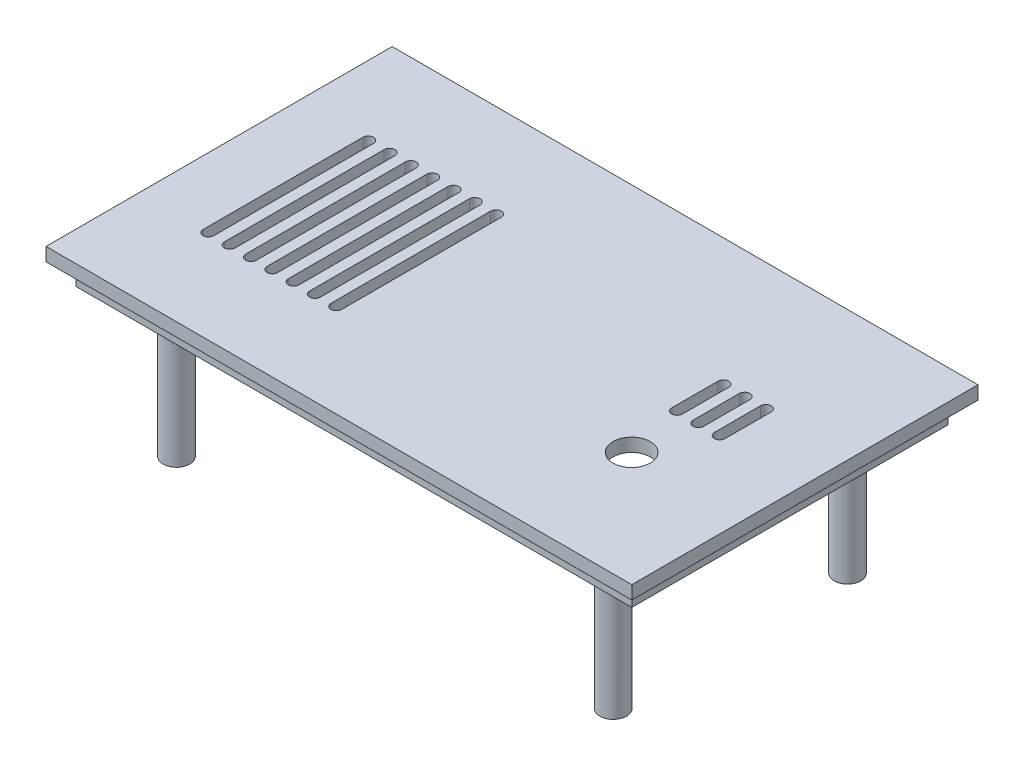
SolidWorks part; units mm, degrees
ref_plane "Front Plane" through (0, 0, 0) normal (0, 0, 1) x (1, 0, 0)
ref_plane "Top Plane" through (0, 0, 0) normal (0, 1, 0) x (1, 0, 0)
ref_plane "Right Plane" through (0, 0, 0) normal (1, 0, 0) x (0, 0, -1)
sketch "Croquis_tapa" plane through (0, 0, 0) normal (0, 1, 0) x (1, 0, 0)
  line L1 (-55, -32.5) -> (55, -32.5)
  line L2 (-55, -32.5) -> (-55, 32.5)
  line L3 (-55, 32.5) -> (55, 32.5)
  line L4 (55, -32.5) -> (55, 32.5)
  line L5 (-55, -32.5) -> (55, 32.5) construction
  line L6 (-55, 32.5) -> (55, -32.5) construction
  point P0 (0, 0)
  dimension "D1" = 110
  dimension "D2" = 65
extrude "Tapa" add sketch "Croquis_tapa" along normal blind 2.5
sketch "Croquis_pestana" plane through (0, 0, 0) normal (0, 1, 0) x (1, 0, 0)
  line L1 (-52.2, -29.7) -> (52.2, -29.7)
  line L2 (-52.2, -29.7) -> (-52.2, 29.7)
  line L3 (-52.2, 29.7) -> (52.2, 29.7)
  line L4 (52.2, -29.7) -> (52.2, 29.7)
  line L5 (-52.2, -29.7) -> (52.2, 29.7) construction
  line L6 (-52.2, 29.7) -> (52.2, -29.7) construction
  dimension "D1" = 104.4
  dimension "D2" = 59.4
extrude "Pestana" add sketch "Croquis_pestana" against normal blind 4
sketch "Croquis_pestana_hueco" plane through (0, 0, 0) normal (0, 1, 0) x (1, 0, 0)
  line L1 (-50.7, -28.2) -> (50.7, -28.2)
  line L2 (-50.7, -28.2) -> (-50.7, 28.2)
  line L3 (-50.7, 28.2) -> (50.7, 28.2)
  line L4 (50.7, -28.2) -> (50.7, 28.2)
  line L5 (-50.7, -28.2) -> (50.7, 28.2) construction
  line L6 (-50.7, 28.2) -> (50.7, -28.2) construction
  dimension "D1" = 101.4
  dimension "D2" = 56.4
extrude "Pestana_hueco" cut sketch "Croquis_pestana_hueco" against normal blind 4
sketch "Croquis_postes" plane through (0, 0, 0) normal (0, 1, 0) x (1, 0, 0)
  circle A0 centre (-41, 22) radius 2.5
  circle A1 centre (-41, -22) radius 2.5
  circle A2 centre (41, 22) radius 2.5
  circle A3 centre (41, -22) radius 2.5
  dimension "D1" = 5
extrude "Postes_PCB" add sketch "Croquis_postes" against normal blind 29.9
sketch "Croquis_ventana_y_ventilas" plane through (0, 0, 0) normal (0, 1, 0) x (1, 0, 0)
  line L0 (31, 0) -> (31, 8.68) construction
  line L1 (30, 0) -> (30, 8.68)
  line L2 (32, 0) -> (32, 8.68)
  line L3 (35, 0) -> (35, 8.68) construction
  line L4 (34, 0) -> (34, 8.68)
  line L5 (36, 0) -> (36, 8.68)
  line L6 (39, 0) -> (39, 8.68) construction
  line L7 (38, 0) -> (38, 8.68)
  line L8 (40, 0) -> (40, 8.68)
  line L9 (-18, -15) -> (-18, 15) construction
  line L10 (-19, -15) -> (-19, 15)
  line L11 (-17, -15) -> (-17, 15)
  line L12 (-22, -15) -> (-22, 15) construction
  line L13 (-23, -15) -> (-23, 15)
  line L14 (-21, -15) -> (-21, 15)
  line L15 (-26, -15) -> (-26, 15) construction
  line L16 (-27, -15) -> (-27, 15)
  line L17 (-25, -15) -> (-25, 15)
  line L18 (-30, -15) -> (-30, 15) construction
  line L19 (-31, -15) -> (-31, 15)
  line L20 (-29, -15) -> (-29, 15)
  line L21 (-34, -15) -> (-34, 15) construction
  line L22 (-35, -15) -> (-35, 15)
  line L23 (-33, -15) -> (-33, 15)
  line L24 (-38, -15) -> (-38, 15) construction
  line L25 (-39, -15) -> (-39, 15)
  line L26 (-37, -15) -> (-37, 15)
  line L27 (-42, -15) -> (-42, 15) construction
  line L28 (-43, -15) -> (-43, 15)
  line L29 (-41, -15) -> (-41, 15)
  circle A0 centre (33.46, -11) radius 3.5
  arc A1 (30, 0) -> (32, 0) centre (31, 0) ccw
  arc A2 (32, 8.68) -> (30, 8.68) centre (31, 8.68) ccw
  arc A3 (34, 0) -> (36, 0) centre (35, 0) ccw
  arc A4 (36, 8.68) -> (34, 8.68) centre (35, 8.68) ccw
  arc A5 (38, 0) -> (40, 0) centre (39, 0) ccw
  arc A6 (40, 8.68) -> (38, 8.68) centre (39, 8.68) ccw
  arc A7 (-19, -15) -> (-17, -15) centre (-18, -15) ccw
  arc A8 (-17, 15) -> (-19, 15) centre (-18, 15) ccw
  arc A9 (-23, -15) -> (-21, -15) centre (-22, -15) ccw
  arc A10 (-21, 15) -> (-23, 15) centre (-22, 15) ccw
  arc A11 (-27, -15) -> (-25, -15) centre (-26, -15) ccw
  arc A12 (-25, 15) -> (-27, 15) centre (-26, 15) ccw
  arc A13 (-31, -15) -> (-29, -15) centre (-30, -15) ccw
  arc A14 (-29, 15) -> (-31, 15) centre (-30, 15) ccw
  arc A15 (-35, -15) -> (-33, -15) centre (-34, -15) ccw
  arc A16 (-33, 15) -> (-35, 15) centre (-34, 15) ccw
  arc A17 (-39, -15) -> (-37, -15) centre (-38, -15) ccw
  arc A18 (-37, 15) -> (-39, 15) centre (-38, 15) ccw
  arc A19 (-43, -15) -> (-41, -15) centre (-42, -15) ccw
  arc A20 (-41, 15) -> (-43, 15) centre (-42, 15) ccw
  point P4 (31, 4.34)
  point P9 (35, 4.34)
  point P16 (39, 4.34)
  point P23 (-18, 0)
  point P30 (-22, 0)
  point P37 (-26, 0)
  point P44 (-30, 0)
  point P51 (-34, 0)
  point P58 (-38, 0)
  point P65 (-42, 0)
  point P72 (0, 0)
  dimension "D1" = 7
extrude "Ventana_LDR_y_ventilas" cut sketch "Croquis_ventana_y_ventilas" along normal through all and the other way through all
